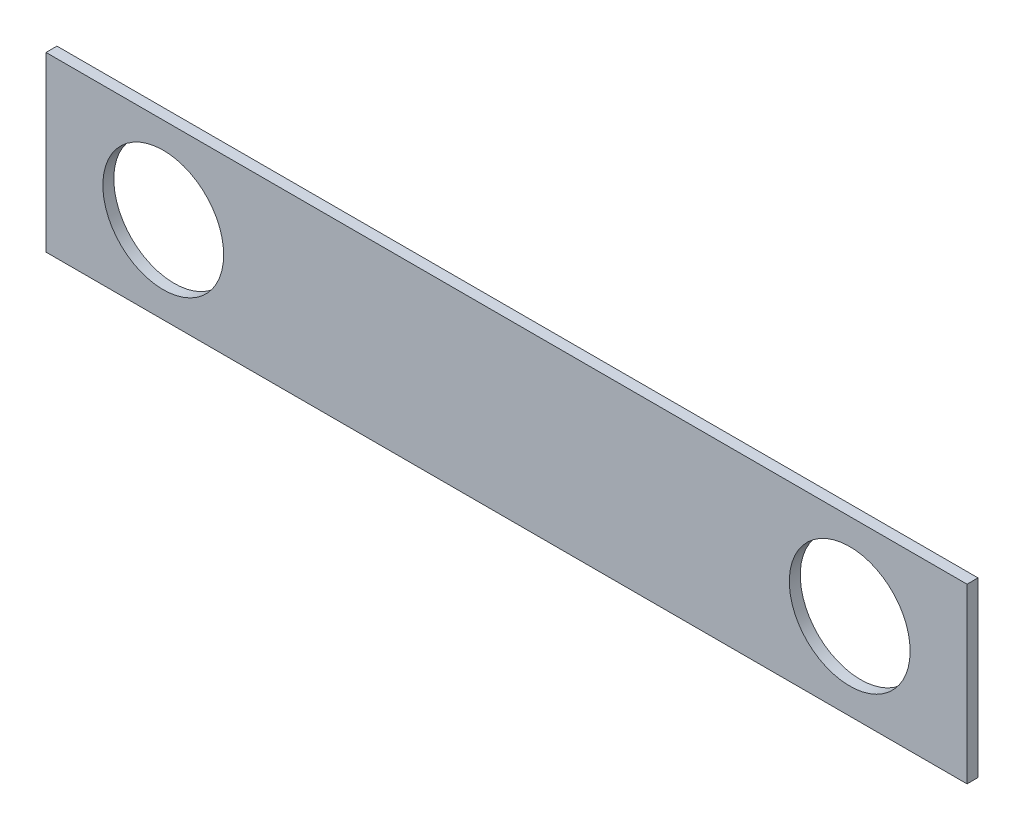
SolidWorks part; units mm, degrees
ref_plane "Front Plane" through (0, 0, 0) normal (0, 0, 1) x (1, 0, 0)
ref_plane "Top Plane" through (0, 0, 0) normal (0, 1, 0) x (1, 0, 0)
ref_plane "Right Plane" through (0, 0, 0) normal (1, 0, 0) x (0, 0, -1)
sketch "Sketch1" plane through (0, 0, 0) normal (0, 0, 1) x (1, 0, 0)
  line L1 (0, 0) -> (63.9, 0)
  line L2 (0, 0) -> (0, 12)
  line L3 (0, 12) -> (63.9, 12)
  line L4 (63.9, 0) -> (63.9, 12)
  dimension "D1" = 63.9
  dimension "D2" = 12
extrude "Boss-Extrude1" add sketch "Sketch1" along normal blind 0.76
sketch "Sketch3" plane through (0, 0, 0.76) normal (0, 0, 1) x (1, 0, 0)
  line L0 (0, 6) -> (63.9, 6) construction
  line L1 (0, 12) -> (0, 0) construction
  line L2 (63.9, 0) -> (63.9, 12) construction
  line L3 (8.135, 6) -> (0, 6) construction
  line L4 (55.76, 6) -> (63.9, 6) construction
  line L6 (63.9, 12) -> (0, 12) construction
  circle A0 centre (8.135, 6) radius 4.191
  circle A1 centre (55.76, 6) radius 4.191
  dimension "D1" = 47.625
  dimension "D2" = 8.382
  dimension "D3" = 8.135
  dimension "D4" = 6
extrude "Cut-Extrude1" cut sketch "Sketch3" against normal through all
